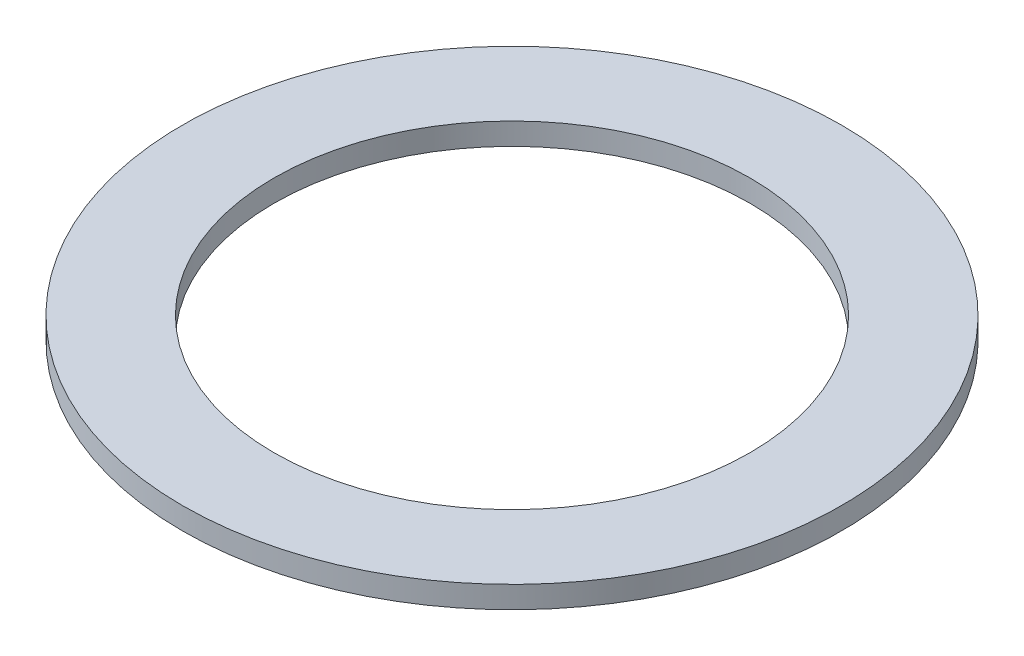
SolidWorks part; units mm, degrees
ref_plane "Front Plane" through (0, 0, 0) normal (0, 0, 1) x (1, 0, 0)
ref_plane "Top Plane" through (0, 0, 0) normal (0, 1, 0) x (1, 0, 0)
ref_plane "Right Plane" through (0, 0, 0) normal (1, 0, 0) x (0, 0, -1)
sketch "Sketch1" plane through (0, 0, 0) normal (0, 1, 0) x (1, 0, 0)
  circle A0 centre (0, 0) radius 45
  circle A1 centre (0, 0) radius 32.5
  dimension "D1" = 90
  dimension "D2" = 65
extrude "Boss-Extrude1" add sketch "Sketch1" along normal blind 3
